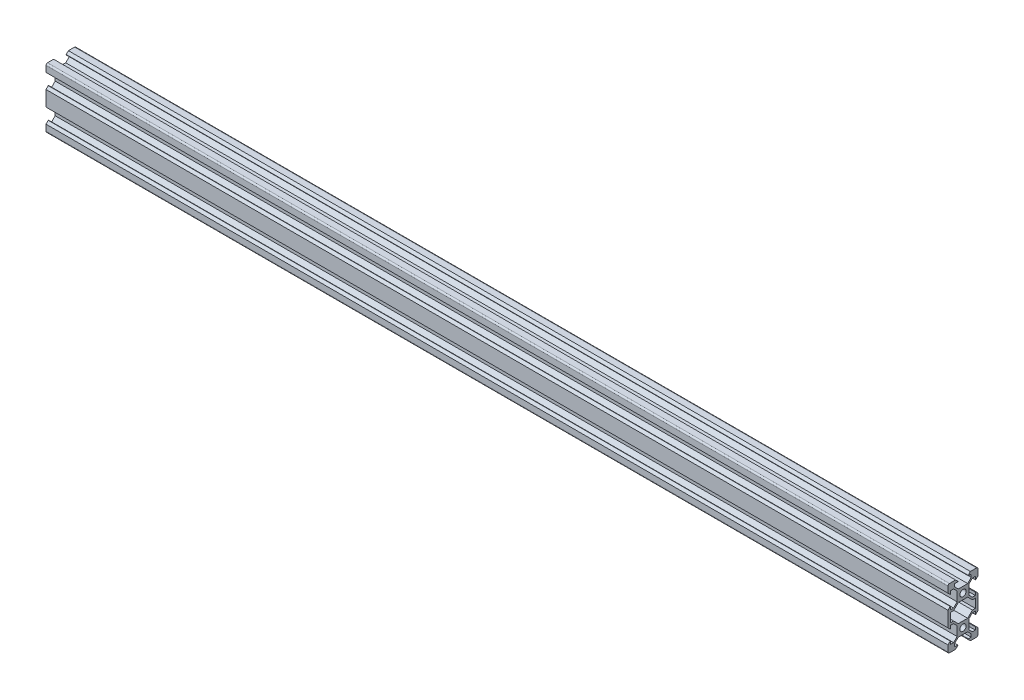
SolidWorks part; units mm, degrees
ref_plane "Front Plane" through (0, 0, 0) normal (0, 0, 1) x (1, 0, 0)
ref_plane "Top Plane" through (0, 0, 0) normal (0, 1, 0) x (1, 0, 0)
ref_plane "Right Plane" through (0, 0, 0) normal (1, 0, 0) x (0, 0, -1)
sketch "Sketch1" plane through (0, 0, 0) normal (0, 1, 0) x (1, 0, 0)
  line L0 (-300.339, 0) -> (300.339, 0)
  point P4 (0, 0)
  dimension "D1" = 600.678
other "Vslot2040 2040(1)"
ref_plane "Plane1" through (-300.339, 0, 0) normal (1, 0, 0) x (0, 0, -1)
sketch "Sketch11" plane through (-300.339, 0, 0) normal (1, 0, 0) x (0, 0, -1)
  line L12 (3.125, 6.1) -> (6.275, 2.95)
  line L13 (6.275, 2.95) -> (8.2, 2.95)
  line L14 (8.2, 2.95) -> (8.2, -2.95)
  line L15 (8.2, -2.95) -> (6.275, -2.95)
  line L16 (3.125, -6.1) -> (6.275, -2.95)
  line L17 (3.125, -6.1) -> (-3.125, -6.1)
  line L18 (-3.125, -6.1) -> (-6.275, -2.95)
  line L19 (-8.2, -2.95) -> (-6.275, -2.95)
  line L20 (-8.2, 2.95) -> (-8.2, -2.95)
  line L21 (-6.275, 2.95) -> (-8.2, 2.95)
  line L22 (-3.125, 6.1) -> (-6.275, 2.95)
  line L23 (3.125, 6.1) -> (-3.125, 6.1)
  line L128 (5.5, -18.2) -> (3.6078, -18.2)
  line L129 (3.4664, -18.5414) -> (4.925, -20)
  line L130 (4.925, -20) -> (9, -20)
  line L131 (10, -19) -> (10, -14.925)
  line L132 (10, -14.925) -> (8.5414, -13.4664)
  line L133 (8.2, -13.6078) -> (8.2, -15.5)
  line L134 (8.2, -15.5) -> (6.275, -15.5)
  line L135 (6.275, -15.5) -> (3.9, -13.125)
  line L136 (3.9, -13.125) -> (3.9, -6.875)
  line L137 (3.9, -6.875) -> (6.275, -4.5)
  line L138 (6.275, -4.5) -> (8.2, -4.5)
  line L139 (8.2, -4.5) -> (8.2, -6.3922)
  line L140 (8.5414, -6.5336) -> (10, -5.075)
  line L141 (10, -5.075) -> (10, 5.075)
  line L142 (10, 5.075) -> (8.5414, 6.5336)
  line L143 (8.2, 6.3922) -> (8.2, 4.5)
  line L144 (8.2, 4.5) -> (6.275, 4.5)
  line L145 (6.275, 4.5) -> (3.9, 6.875)
  line L146 (3.9, 6.875) -> (3.9, 13.125)
  line L147 (3.9, 13.125) -> (6.275, 15.5)
  line L148 (6.275, 15.5) -> (8.2, 15.5)
  line L149 (8.2, 15.5) -> (8.2, 13.6078)
  line L150 (8.5414, 13.4664) -> (10, 14.925)
  line L151 (10, 14.925) -> (10, 19)
  line L152 (9, 20) -> (4.925, 20)
  line L153 (4.925, 20) -> (3.4664, 18.5414)
  line L154 (3.6078, 18.2) -> (5.5, 18.2)
  line L155 (5.5, 18.2) -> (5.5, 16.275)
  line L156 (5.5, 16.275) -> (3.125, 13.9)
  line L157 (3.125, 13.9) -> (-3.125, 13.9)
  line L158 (-3.125, 13.9) -> (-5.5, 16.275)
  line L159 (-5.5, 16.275) -> (-5.5, 18.2)
  line L160 (-5.5, 18.2) -> (-3.6078, 18.2)
  line L161 (-3.4664, 18.5414) -> (-4.925, 20)
  line L162 (-4.925, 20) -> (-9, 20)
  line L163 (-10, 19) -> (-10, 14.925)
  line L164 (-10, 14.925) -> (-8.5414, 13.4664)
  line L165 (-8.2, 13.6078) -> (-8.2, 15.5)
  line L166 (-8.2, 15.5) -> (-6.275, 15.5)
  line L167 (-6.275, 15.5) -> (-3.9, 13.125)
  line L168 (-3.9, 13.125) -> (-3.9, 6.875)
  line L169 (-3.9, 6.875) -> (-6.275, 4.5)
  line L170 (-6.275, 4.5) -> (-8.2, 4.5)
  line L171 (-8.2, 4.5) -> (-8.2, 6.3922)
  line L172 (-8.5414, 6.5336) -> (-10, 5.075)
  line L173 (-10, 5.075) -> (-10, -5.075)
  line L174 (-10, -5.075) -> (-8.5414, -6.5336)
  line L175 (-8.2, -6.3922) -> (-8.2, -4.5)
  line L176 (-8.2, -4.5) -> (-6.275, -4.5)
  line L177 (-6.275, -4.5) -> (-3.9, -6.875)
  line L178 (-3.9, -6.875) -> (-3.9, -13.125)
  line L179 (-3.9, -13.125) -> (-6.275, -15.5)
  line L180 (-6.275, -15.5) -> (-8.2, -15.5)
  line L181 (-8.2, -15.5) -> (-8.2, -13.6078)
  line L182 (-8.5414, -13.4664) -> (-10, -14.925)
  line L183 (-10, -14.925) -> (-10, -19)
  line L184 (-9, -20) -> (-4.925, -20)
  line L185 (-4.925, -20) -> (-3.4664, -18.5414)
  line L186 (-3.6078, -18.2) -> (-5.5, -18.2)
  line L187 (-5.5, -18.2) -> (-5.5, -16.275)
  line L188 (-5.5, -16.275) -> (-3.125, -13.9)
  line L189 (-3.125, -13.9) -> (3.125, -13.9)
  line L190 (3.125, -13.9) -> (5.5, -16.275)
  line L191 (5.5, -16.275) -> (5.5, -18.2)
  circle A2 centre (0, -10) radius 2.1
  circle A3 centre (0, 10) radius 2.1
  arc A32 (3.6078, -18.2) -> (3.4664, -18.5414) centre (3.6078, -18.4) ccw
  arc A33 (9, -20) -> (10, -19) centre (9, -19) ccw
  arc A34 (8.5414, -13.4664) -> (8.2, -13.6078) centre (8.4, -13.6078) ccw
  arc A35 (8.2, -6.3922) -> (8.5414, -6.5336) centre (8.4, -6.3922) ccw
  arc A36 (8.5414, 6.5336) -> (8.2, 6.3922) centre (8.4, 6.3922) ccw
  arc A37 (8.2, 13.6078) -> (8.5414, 13.4664) centre (8.4, 13.6078) ccw
  arc A38 (10, 19) -> (9, 20) centre (9, 19) ccw
  arc A39 (3.4664, 18.5414) -> (3.6078, 18.2) centre (3.6078, 18.4) ccw
  arc A40 (-3.6078, 18.2) -> (-3.4664, 18.5414) centre (-3.6078, 18.4) ccw
  arc A41 (-9, 20) -> (-10, 19) centre (-9, 19) ccw
  arc A42 (-8.5414, 13.4664) -> (-8.2, 13.6078) centre (-8.4, 13.6078) ccw
  arc A43 (-8.2, 6.3922) -> (-8.5414, 6.5336) centre (-8.4, 6.3922) ccw
  arc A44 (-8.5414, -6.5336) -> (-8.2, -6.3922) centre (-8.4, -6.3922) ccw
  arc A45 (-8.2, -13.6078) -> (-8.5414, -13.4664) centre (-8.4, -13.6078) ccw
  arc A46 (-10, -19) -> (-9, -20) centre (-9, -19) ccw
  arc A47 (-3.4664, -18.5414) -> (-3.6078, -18.2) centre (-3.6078, -18.4) ccw
  point P43 (0, 0)
